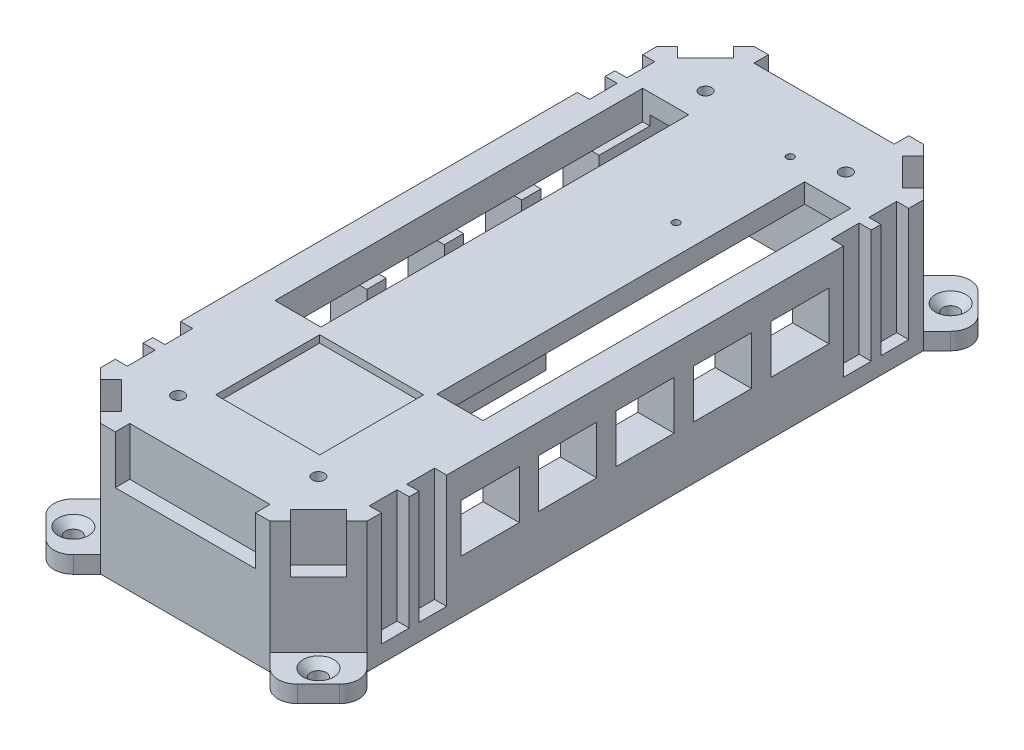
SolidWorks part; units mm, degrees
ref_plane "Front Plane" through (0, 0, 0) normal (0, 0, 1) x (1, 0, 0)
ref_plane "Top Plane" through (0, 0, 0) normal (0, 1, 0) x (1, 0, 0)
ref_plane "Right Plane" through (0, 0, 0) normal (1, 0, 0) x (0, 0, -1)
sketch "Sketch2" plane through (0, 0, 0) normal (0, 1, 0) x (1, 0, 0)
  line L1 (27.5, -67.5) -> (-27.5, -67.5)
  line L2 (27.5, -67.5) -> (27.5, 67.5)
  line L3 (27.5, 67.5) -> (-27.5, 67.5)
  line L4 (-27.5, -67.5) -> (-27.5, 67.5)
  line L5 (27.5, -67.5) -> (-27.5, 67.5) construction
  line L6 (27.5, 67.5) -> (-27.5, -67.5) construction
  point P0 (0, 0)
  dimension "D1" = 135
  dimension "D2" = 55
extrude "Boss-Extrude1" add sketch "Sketch2" along normal blind 27
sketch "Sketch3" plane through (0, 0, 0) normal (0, -1, 0) x (1, 0, 0)
  line L5 (-27.5, 67.5) -> (27.5, 67.5) construction
  line L6 (-20, -60) -> (20, -60)
  line L8 (-20, -60) -> (-20, 60)
  line L9 (-20, 60) -> (20, 60)
  line L10 (20, -60) -> (20, 60)
  line L11 (-20, -60) -> (20, 60) construction
  line L12 (-20, 60) -> (20, -60) construction
  line L13 (27.5, 67.5) -> (27.5, -67.5) construction
  point P0 (0, 0)
  point P1 (0, 0)
  dimension "D1" = 7.5
  dimension "D2" = 7.5
extrude "Cut-Extrude1" cut sketch "Sketch3" against normal blind 23
ref_plane "Plane1" through (0, 1, 0) normal (0, -1, 0) x (-1, 0, 0)
sketch "Sketch19" plane through (27.5, 0, 0) normal (1, 0, 0) x (0, 0, -1)
  line L0 (-67.5, 27) -> (-67.5, 0) construction
  line L1 (-38, 21) -> (-26, 21)
  line L2 (-38, 21) -> (-38, 11)
  line L3 (-38, 11) -> (-26, 11)
  line L4 (-26, 21) -> (-26, 11)
  line L5 (-67.5, 27) -> (67.5, 27) construction
  line L6 (-22, 21) -> (-22, 11)
  line L7 (-22, 21) -> (-10, 21)
  line L8 (-10, 21) -> (-10, 11)
  line L9 (-22, 11) -> (-10, 11)
  line L10 (-6, 21) -> (-6, 11)
  line L11 (-6, 21) -> (6, 21)
  line L12 (6, 21) -> (6, 11)
  line L13 (-6, 11) -> (6, 11)
  line L14 (10, 21) -> (10, 11)
  line L15 (10, 21) -> (22, 21)
  line L16 (22, 21) -> (22, 11)
  line L17 (10, 11) -> (22, 11)
  line L18 (26, 21) -> (26, 11)
  line L19 (26, 21) -> (38, 21)
  line L20 (38, 21) -> (38, 11)
  line L21 (26, 11) -> (38, 11)
  dimension "D1" = 12
  dimension "D2" = 29.5
  dimension "D3" = 6
  dimension "D4" = 10
  dimension "D6" = 4
  dimension "D5" = 5
extrude "Cut-Extrude7" cut sketch "Sketch19" against normal blind 55
sketch "Sketch20" plane through (0, 27, 0) normal (0, 1, 0) x (1, 0, 0)
  line L0 (-27.5, 67.5) -> (-27.5, -67.5) construction
  line L1 (27.5, 67.5) -> (-27.5, 67.5) construction
  line L2 (-27.5, 67.5) -> (-27.5, -67.5) construction
  line L3 (0, -14.85) -> (0, 14.85) construction
  line L4 (-14.85, 0) -> (14.85, 0) construction
  line L7 (-21.5, -27.5) -> (-12, -27.5)
  line L8 (-21.5, -27.5) -> (-21.5, 48.5)
  line L9 (-21.5, 48.5) -> (-12, 48.5)
  line L10 (-12, -27.5) -> (-12, 48.5)
  line L11 (-21.5, -27.5) -> (-12, 48.5) construction
  line L12 (-21.5, 48.5) -> (-12, -27.5) construction
  line L14 (21.5, 48.5) -> (12, 48.5)
  line L15 (12, -27.5) -> (12, 48.5)
  line L16 (21.5, -27.5) -> (12, -27.5)
  line L17 (21.5, -27.5) -> (21.5, 48.5)
  circle A0 centre (-14.5, 54.5) radius 1.25
  circle A1 centre (14.5, 54.5) radius 1.25
  circle A2 centre (14.5, -54.5) radius 1.25
  circle A3 centre (-14.5, -54.5) radius 1.25
  point P16 (-16.75, 10.5)
  point P28 (-14.5, 54.5)
  dimension "D3" = 2.5
  dimension "D4" = 6
  dimension "D1" = 13
  dimension "D2" = 13
  dimension "D5" = 6
  dimension "D6" = 27
  dimension "D7" = 12
extrude "Cut-Extrude8" cut sketch "Sketch20" against normal blind 6
chamfer "Chamfer1" distance 10 angle 45 4 edges at (27.5, 13.5, 67.5) (-27.5, 13.5, 67.5) (-27.5, 13.5, -67.5) (27.5, 13.5, -67.5)
sketch "Sketch22" plane through (0, 27, 0) normal (0, 1, 0) x (1, 0, 0)
  line L0 (12, 39.7) -> (-12, 39.7)
  line L1 (12, 48.5) -> (12, -27.5) construction
  line L2 (-12, -27.5) -> (-12, 48.5) construction
  circle A0 centre (6, 51.5) radius 0.75
  circle A1 centre (14.5, 54.5) radius 1.25 construction
  circle A2 centre (6, 27.9) radius 0.75
  dimension "D1" = 1.5
  dimension "D2" = 3
  dimension "D3" = 11.8
  dimension "D4" = 6
extrude "Cut-Extrude10" cut sketch "Sketch22" against normal blind 10 contours A0 | A2
sketch "Sketch23" plane through (0, 27, 0) normal (0, 1, 0) x (1, 0, 0)
  line L0 (0, -14.85) -> (0, 14.85) construction
  line L1 (-10.75, -29) -> (10.75, -29)
  line L2 (-10.75, -29) -> (-10.75, -50.5)
  line L3 (-10.75, -50.5) -> (10.75, -50.5)
  line L4 (10.75, -29) -> (10.75, -50.5)
  line L5 (-10.75, -29) -> (10.75, -50.5) construction
  line L6 (-10.75, -50.5) -> (10.75, -29) construction
  circle A0 centre (-14.5, -54.5) radius 1.25 construction
  point P0 (0, -39.75)
  dimension "D1" = 21.5
  dimension "D2" = 21.5
  dimension "D3" = 4
extrude "Cut-Extrude11" cut sketch "Sketch23" against normal blind 1.5
sketch "Sketch24" plane through (0, 23, 0) normal (0, -1, 0) x (1, 0, 0)
  line L5 (20, 60) -> (-20, 60) construction
  line L9 (0, -14.85) -> (0, 14.85) construction
  line L10 (8, 25) -> (-8, 25)
  line L11 (8, 25) -> (8, 1)
  line L12 (8, 1) -> (-8, 1)
  line L13 (-8, 25) -> (-8, 1)
  point P0 (0, 0)
  dimension "D1" = 24
  dimension "D2" = 8
  dimension "D3" = 8
  dimension "D4" = 35
extrude "Boss-Extrude2" add sketch "Sketch24" along normal blind 7
sketch "Sketch26" plane through (0, 0, 25) normal (0, 0, 1) x (1, 0, 0)
  line L0 (8, 23) -> (-8, 23) construction
  line L1 (5.5, 23) -> (-5.5, 23)
  line L2 (5.5, 23) -> (5.5, 18.5)
  line L3 (5.5, 18.5) -> (-5.5, 18.5)
  line L4 (-5.5, 23) -> (-5.5, 18.5)
  line L5 (8, 16) -> (8, 23) construction
  line L6 (8, 16) -> (-8, 16) construction
  line L7 (-8, 16) -> (-8, 23) construction
  dimension "D1" = 2.5
  dimension "D2" = 2.5
  dimension "D3" = 2.5
extrude "Cut-Extrude13" cut sketch "Sketch26" against normal blind 24
sketch "Sketch27" plane through (-42.5, 0, 42.5) normal (-0.7071, 0, 0.7071) x (0.7071, 0, 0.7071)
  line L0 (35.3553, 27) -> (35.3553, 0) construction
  line L1 (21.2132, 0) -> (35.3553, 0)
  line L2 (21.2132, 0) -> (21.2132, 3.5)
  line L3 (21.2132, 3.5) -> (35.3553, 3.5)
  line L4 (35.3553, 0) -> (35.3553, 3.5)
  dimension "D1" = 3.5
extrude "Boss-Extrude3" add sketch "Sketch27" along normal blind 8
mirror "Mirror1" about plane through (0, 0, 0) normal (1, 0, 0) of "Boss-Extrude3"
sketch "Sketch31" plane through (0, 0, 67.5) normal (0, 0, 1) x (1, 0, 0)
  line L0 (-17.5, 27) -> (17.5, 27) construction
  line L1 (-14.5, 27) -> (14.5, 27)
  line L2 (-14.5, 27) -> (-14.5, 17)
  line L3 (-14.5, 17) -> (14.5, 17)
  line L4 (14.5, 27) -> (14.5, 17)
  line L5 (-17.5, 27) -> (-17.5, 3.5) construction
  line L6 (17.5, 3.5) -> (17.5, 27) construction
  dimension "D1" = 3
  dimension "D2" = 3
  dimension "D3" = 10
extrude "Cut-Extrude17" cut sketch "Sketch31" against normal blind 3
sketch "Sketch32" plane through (42.5, 0, 42.5) normal (0.7071, 0, 0.7071) x (0.7071, 0, -0.7071)
  line L0 (-35.3553, 27) -> (-21.2132, 27) construction
  line L1 (-32.3553, 27) -> (-24.2132, 27)
  line L2 (-32.3553, 27) -> (-32.3553, 17)
  line L3 (-32.3553, 17) -> (-24.2132, 17)
  line L4 (-24.2132, 27) -> (-24.2132, 17)
  line L5 (-35.3553, 3.5) -> (-35.3553, 27) construction
  line L6 (-21.2132, 27) -> (-21.2132, 3.5) construction
  dimension "D1" = 3
  dimension "D2" = 3
  dimension "D3" = 10
extrude "Cut-Extrude18" cut sketch "Sketch32" against normal blind 3
mirror "Mirror7" about plane through (0, 0, 0) normal (1, 0, 0) of "Cut-Extrude18"
mirror "Mirror8" about plane through (0, 0, 0) normal (0, 0, 1) of "Mirror7", "Cut-Extrude18"
mirror "Mirror9" about plane through (0, 0, 0) normal (0, 0, 1) of "Cut-Extrude17"
sketch "Sketch41" plane through (0, 3.5, 0) normal (0, 1, 0) x (1, 0, 0)
  line L0 (33.1569, -63.1569) -> (27.5, -57.5) construction
  line L1 (19.6213, -65.3787) -> (25.3787, -59.6213) construction
  point P0 (25.3292, -65.3277)
  dimension "D1" = 7.07
  dimension "D2" = 4
hole_wizard "CSK for M3 Flat Head Machine Screw2" positions "3DSketch2" profile "Sketch42" countersink size "M3" standard "ANSI Metric" end condition through all
sketch3d "3DSketch2"
  point P0 (25.3292, 3.5, 65.3277)
sketch "Sketch42" plane through (25.3292, 3.5, 65.3277) normal (1, 0, 0) x (0, 0, 1)
  line L0 (0, 0) -> (0, 3.5)
  line L1 (0, 3.5) -> (1.6, 3.5)
  line L2 (1.6, 3.5) -> (1.6, 1.55)
  line L3 (1.6, 1.55) -> (3.15, 0)
  line L5 (3.15, 0) -> (0, 0)
  line L6 (-1.6, 1.55) -> (-3.15, 0) construction
  line L11 (0, -6.35) -> (0, 107.95) construction
  dimension "Thru Hole Dia." = 3.2
  dimension "Thru Hole Depth" = 3.5
  dimension "Near C'Sink Dia." = 6.3
  dimension "Near C'Sink Angle" = 90
fillet "Fillet3" radius 4 2 edges at (23.1569, 1.75, 73.1569) (33.1569, 1.75, 63.1569)
sketch "Sketch43" plane through (0, 3.5, 0) normal (0, 1, 0) x (1, 0, 0)
  line L0 (-23.1569, -73.1569) -> (-17.5, -67.5) construction
  line L1 (-17.5, -67.5) -> (-27.5, -57.5) construction
  point P0 (-25.3277, -65.3292)
  dimension "D1" = 7.07
  dimension "D2" = 4
mirror "Mirror14" about plane through (0, 0, 0) normal (0, 0, 1) of "Fillet3", "Boss-Extrude3", "Mirror1"
sketch "Sketch44" plane through (0, 3.5, 0) normal (0, 1, 0) x (1, 0, 0)
  line L0 (-33.1569, 63.1569) -> (-27.5, 57.5) construction
  line L2 (-17.5, 67.5) -> (-27.5, 57.5) construction
  line L3 (25.9853, 70.3284) -> (30.3284, 65.9853) construction
  line L6 (30.3284, 60.3284) -> (27.5, 57.5) construction
  point P0 (-25.3292, 65.3277)
  point P6 (25.3292, 65.3277)
  dimension "D1" = 7.07
  dimension "D2" = 4
  dimension "D3" = 4
  dimension "D4" = 7.07
fillet "Fillet4" radius 4 4 edges at (-33.1569, 1.75, 63.1569) (-23.1569, 1.75, 73.1569) (-33.1569, 1.75, -63.1569) (-23.1569, 1.75, -73.1569)
hole_wizard "CSK for M3 Flat Head Machine Screw3" positions "3DSketch3" profile "Sketch45" countersink size "M3" standard "ANSI Metric" end condition through all
sketch3d "3DSketch3"
  point P0 (-25.3277, 3.5, 65.3292)
  point P3 (-25.3292, 3.5, -65.3277)
  point P6 (25.3292, 3.5, -65.3277)
sketch "Sketch45" plane through (-25.3277, 3.5, 65.3292) normal (1, 0, 0) x (0, 0, 1)
  line L0 (0, 0) -> (0, 3.5)
  line L1 (0, 3.5) -> (1.6, 3.5)
  line L2 (1.6, 3.5) -> (1.6, 1.55)
  line L3 (1.6, 1.55) -> (3.15, 0)
  line L5 (3.15, 0) -> (0, 0)
  line L6 (-1.6, 1.55) -> (-3.15, 0) construction
  line L11 (0, -6.35) -> (0, 107.95) construction
  dimension "Thru Hole Dia." = 3.2
  dimension "Thru Hole Depth" = 3.5
  dimension "Near C'Sink Dia." = 6.3
  dimension "Near C'Sink Angle" = 90
sketch "Sketch46" plane through (27.5, 0, 0) normal (1, 0, 0) x (0, 0, -1)
  line L0 (-57.5, 27) -> (57.5, 27) construction
  line L1 (-54.5, 27) -> (-48.75, 27)
  line L2 (-54.5, 27) -> (-54.5, 3.5)
  line L3 (-54.5, 3.5) -> (-48.75, 3.5)
  line L4 (-48.75, 27) -> (-48.75, 3.5)
  line L5 (-57.5, 27) -> (-57.5, 3.5) construction
  line L7 (-60.3284, 3.5) -> (-57.5, 3.5) construction
  line L8 (-38, 21) -> (-38, 11) construction
  line L9 (-46.75, 27) -> (-41, 27)
  line L10 (-46.75, 27) -> (-46.75, 3.5)
  line L11 (-46.75, 3.5) -> (-41, 3.5)
  line L12 (-41, 27) -> (-41, 3.5)
  line L13 (0, 14.85) -> (0, -14.85) construction
  line L14 (46.75, 3.5) -> (41, 3.5)
  line L15 (41, 27) -> (41, 3.5)
  line L16 (46.75, 27) -> (41, 27)
  line L17 (46.75, 27) -> (46.75, 3.5)
  line L18 (54.5, 3.5) -> (48.75, 3.5)
  line L19 (48.75, 27) -> (48.75, 3.5)
  line L20 (54.5, 27) -> (48.75, 27)
  line L21 (54.5, 27) -> (54.5, 3.5)
  dimension "D1" = 3
  dimension "D2" = 0
  dimension "D3" = 3
  dimension "D4" = 2
  dimension "D5" = 5.75
extrude "Cut-Extrude20" cut sketch "Sketch46" against normal blind 2.5
mirror "Mirror15" about plane through (0, 0, 0) normal (1, 0, 0) of "Cut-Extrude20"
